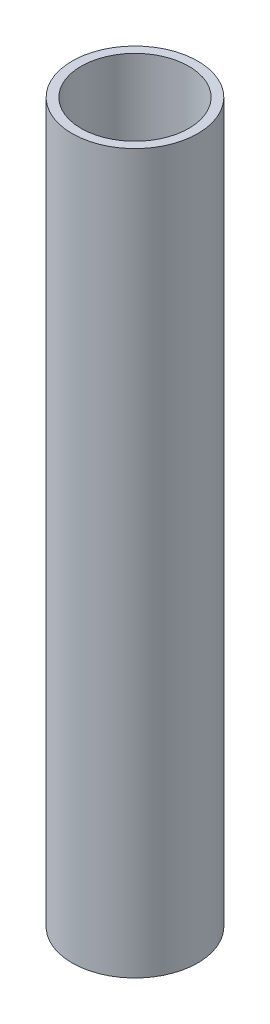
SolidWorks part; units mm, degrees
ref_plane "Front Plane" through (0, 0, 0) normal (0, 0, 1) x (1, 0, 0)
ref_plane "Top Plane" through (0, 0, 0) normal (0, 1, 0) x (1, 0, 0)
ref_plane "Right Plane" through (0, 0, 0) normal (1, 0, 0) x (0, 0, -1)
sketch "Sketch1" plane through (0, 0, 0) normal (0, 1, 0) x (1, 0, 0)
  circle A0 centre (0, 0) radius 60
  circle A1 centre (0, 0) radius 70
extrude "Boss-Extrude1" add sketch "Sketch1" along normal blind 800
